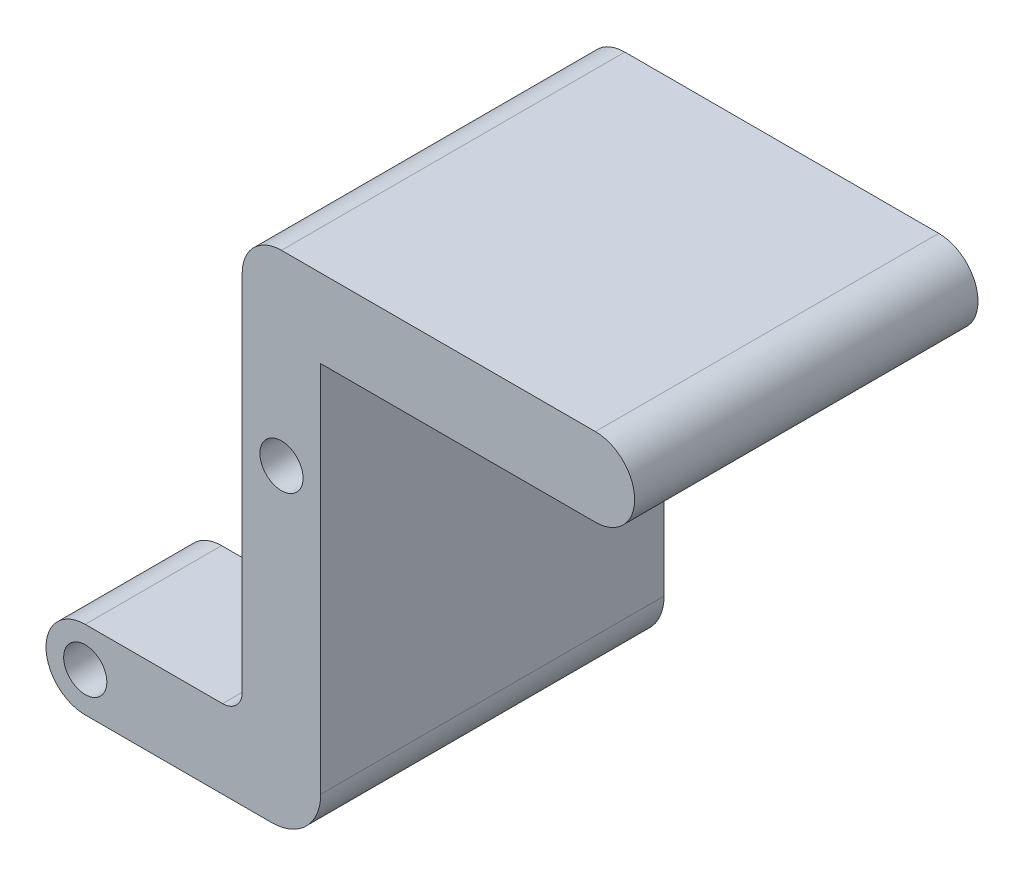
SolidWorks part; units mm, degrees
ref_plane "Front Plane" through (0, 0, 0) normal (0, 0, 1) x (1, 0, 0)
ref_plane "Top Plane" through (0, 0, 0) normal (0, 1, 0) x (1, 0, 0)
ref_plane "Right Plane" through (0, 0, 0) normal (1, 0, 0) x (0, 0, -1)
sketch "Sketch1" plane through (0, 0, 0) normal (0, 0, 1) x (1, 0, 0)
  line L0 (0, 0) -> (-100, 0) construction
  line L1 (0, 0) -> (0, 140) construction
  line L2 (-20, 20) -> (-20, 140)
  line L3 (-20, 20) -> (-100, 20)
  line L4 (20, -20) -> (20, 140)
  line L5 (20, -20) -> (-100, -20)
  arc A0 (-20, 140) -> (20, 140) centre (0, 140) cw
  arc A1 (-100, 20) -> (-100, -20) centre (-100, 0) ccw
  dimension "D1" = 100
  dimension "D2" = 140
  dimension "D3" = 20
  dimension "D4" = 20
extrude "Boss-Extrude1" add sketch "Sketch1" along normal mid plane 175
sketch "Sketch2" plane through (0, 0, 87.5) normal (0, 0, 1) x (1, 0, 0)
  circle A0 centre (-100, 0) radius 11
  circle A1 centre (0, 140) radius 11
  dimension "D1" = 22
extrude "Cut-Extrude1" cut sketch "Sketch2" against normal up to surface (175 mm away) up to face at (-36.6667, 50, -87.5)
fillet "Fillet1" radius 10 1 edges at (-20, 20, 0)
fillet "Fillet2" radius 25 1 edges at (20, -20, 0)
sketch "Sketch3" plane through (0, 0, 0) normal (0, 0, 1) x (1, 0, 0)
  line L1 (-120, 20) -> (-80, 20)
  line L2 (-120, 20) -> (-120, -20)
  line L3 (-120, -20) -> (-80, -20)
  line L4 (-80, 20) -> (-80, -20)
  circle A0 centre (-100, 0) radius 20 construction
  arc A1 (-100, 20) -> (-100, -20) centre (-100, 0) ccw construction
extrude "Cut-Extrude2" cut sketch "Sketch3" against normal blind 18 and the other way blind 18
sketch "Sketch4" plane through (0, 0, -87.5) normal (0, 0, -1) x (-1, 0, 0)
  line L0 (0, 215.09) -> (-160, 215.09) construction
  line L1 (0, 140) -> (0, 215.09) construction
  line L2 (20, 140) -> (20, 215.09)
  line L3 (0, 235.09) -> (-160, 235.09)
  line L4 (-20, 140) -> (-20, 215.09)
  line L5 (0, 195.09) -> (-160, 195.09)
  arc A0 (20, 140) -> (-20, 140) centre (0, 140) cw
  arc A1 (20, 215.09) -> (-20, 215.09) centre (0, 215.09) ccw
  arc A2 (0, 235.09) -> (0, 195.09) centre (0, 215.09) cw
  arc A3 (-160, 235.09) -> (-160, 195.09) centre (-160, 215.09) ccw
  arc M21 (20, 140) -> (-20, 140) centre (0, 140) ccw
  dimension "D3" = 75.09
  dimension "D4" = 160
  dimension "D1" = 20
  dimension "D2" = 20
extrude "Boss-Extrude2" add sketch "Sketch4" against normal up to surface (175 mm away) contours L3 A3 L5 L4 A1 | A2 A1 L4 L5 | L2 A2 L5 L4 M21
